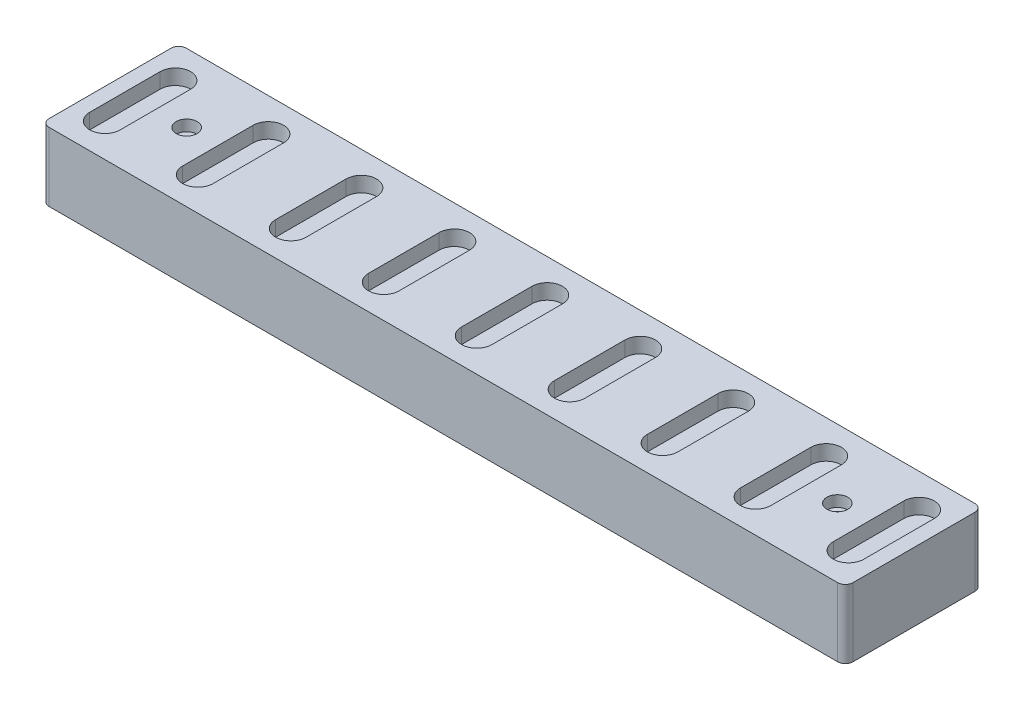
SolidWorks part; units mm, degrees
ref_plane "Front Plane" through (0, 0, 0) normal (0, 0, 1) x (1, 0, 0)
ref_plane "Top Plane" through (0, 0, 0) normal (0, 1, 0) x (1, 0, 0)
ref_plane "Right Plane" through (0, 0, 0) normal (1, 0, 0) x (0, 0, -1)
sketch "Sketch1" plane through (0, 0, 0) normal (0, 1, 0) x (1, 0, 0)
  line L1 (-105.5, -18) -> (105.5, -18)
  line L2 (-105.5, -18) -> (-105.5, 18)
  line L3 (-105.5, 18) -> (105.5, 18)
  line L4 (105.5, -18) -> (105.5, 18)
  line L5 (-105.5, -18) -> (105.5, 18) construction
  line L6 (-105.5, 18) -> (105.5, -18) construction
  point P0 (0, 0)
  dimension "D1" = 211
  dimension "D2" = 36
extrude "Boss-Extrude1" add sketch "Sketch1" along normal blind 18
sketch "Sketch2" plane through (0, 18, 0) normal (0, 1, 0) x (1, 0, 0)
  line L0 (-97.6, 18) -> (-97.6, -18) construction
  line L1 (105.5, 18) -> (-105.5, 18) construction
  line L2 (-105.5, -18) -> (105.5, -18) construction
  line L3 (0, -55) -> (0, 55) construction
  line L4 (-55, 0) -> (55, 0) construction
  line L6 (-101.6, 9.25) -> (-101.6, -9.25)
  line L8 (-93.6, 9.25) -> (-93.6, -9.25)
  line L9 (-101.6, 9.25) -> (-93.6, -9.25) construction
  line L10 (-101.6, -9.25) -> (-93.6, 9.25) construction
  arc A0 (-93.6, 9.25) -> (-101.6, 9.25) centre (-97.6, 9.25) ccw
  arc A1 (-101.6, -9.25) -> (-93.6, -9.25) centre (-97.6, -9.25) ccw
  point P8 (-97.6, 0)
  dimension "D1" = 97.6
  dimension "D2" = 8
  dimension "D3" = 18.5
extrude "Cut-Extrude1" cut sketch "Sketch2" against normal blind 4
pattern_linear "LPattern1" count 9 spacing 24.4 along (1, 0, 0) of "Cut-Extrude1"
ref_plane "Plane1" through (-85.4, 0, 0) normal (-1, 0, 0) x (0, 0, 1)
ref_plane "Plane2" through (85.4, 0, 0) normal (-1, 0, 0) x (0, 0, 1)
hole_wizard "CBORE for M2.5 Socket Head Cap Screw1" positions "Sketch5" profile "Sketch7" counterbore size "M2.5" standard "DIN" end condition through all
sketch "Sketch5" plane through (0, 18, 0) normal (0, 1, 0) x (1, 0, 0)
  line L0 (-9.9, 0) -> (9.9, 0) construction
  line L1 (-85.4, 27.1042) -> (-85.4, -27.1042) construction
  line L2 (85.4, 26.708) -> (85.4, -26.708) construction
  point P21 (-85.4, 0)
  point P23 (85.4, 0)
sketch "Sketch7" plane through (-85.4, 18, 0) normal (1, 0, 0) x (0, 0, 1)
  line L0 (0, 0) -> (0, 18)
  line L1 (0, 18) -> (1.45, 18)
  line L3 (1.45, 18) -> (1.45, 2.9)
  line L4 (1.45, 2.9) -> (2.75, 2.9)
  line L5 (2.75, 2.9) -> (2.75, 0)
  line L7 (2.75, 0) -> (0, 0)
  line L11 (0, -6.35) -> (0, 107.95) construction
  dimension "Thru Hole Dia." = 2.9
  dimension "Thru Hole Depth" = 18
  dimension "C'Bore Dia." = 5.5
  dimension "C'Bore Depth" = 2.9
fillet "Fillet1" radius 2 4 edges at (-105.5, 9, -18) (105.5, 9, -18) (105.5, 9, 18) (-105.5, 9, 18)
